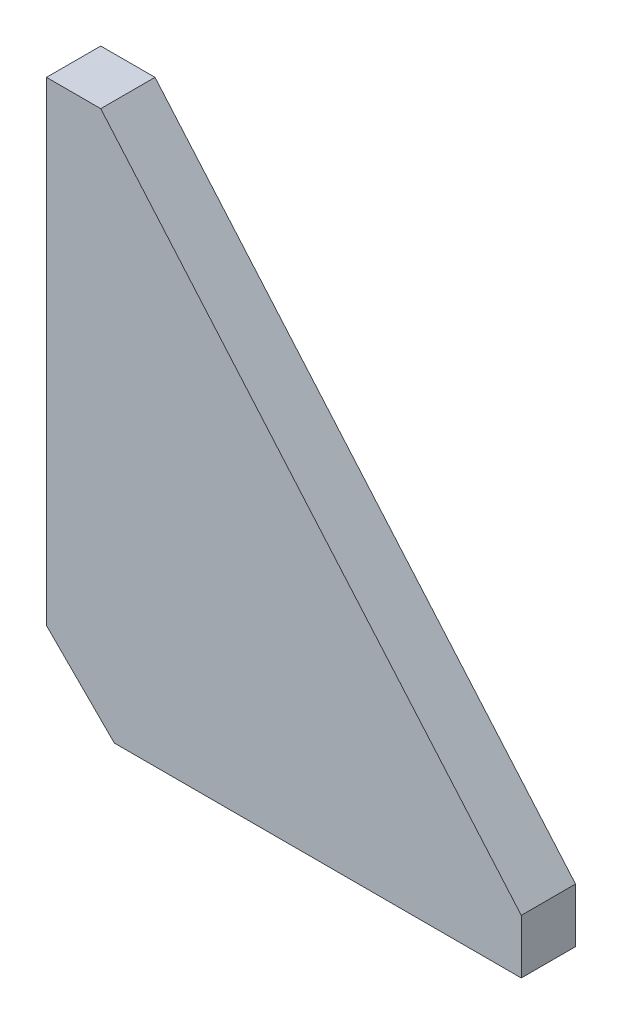
SolidWorks part; units mm, degrees
material "AISI 304"
ref_plane "Спереди" through (0, 0, 0) normal (0, 0, 1) x (1, 0, 0)
ref_plane "Сверху" through (0, 0, 0) normal (0, 1, 0) x (1, 0, 0)
ref_plane "Справа" through (0, 0, 0) normal (1, 0, 0) x (0, 0, -1)
sketch "Эскиз1" plane through (0, 0, 0) normal (0, 0, 1) x (1, 0, 0)
  line L0 (0, 0) -> (0, 80)
  line L1 (8, 80) -> (70, 8)
  line L2 (70, 0) -> (0, 0)
  line L3 (70, 0) -> (70, 8)
  line L4 (8, 80) -> (0, 80)
  dimension "D1" = 70
  dimension "D2" = 8
  dimension "D3" = 80
extrude "Бобышка-Вытянуть1" add sketch "Эскиз1" along normal mid plane 8
chamfer "Фаска1" distance 10 angle 45 1 edges at (0, 0, 0)
